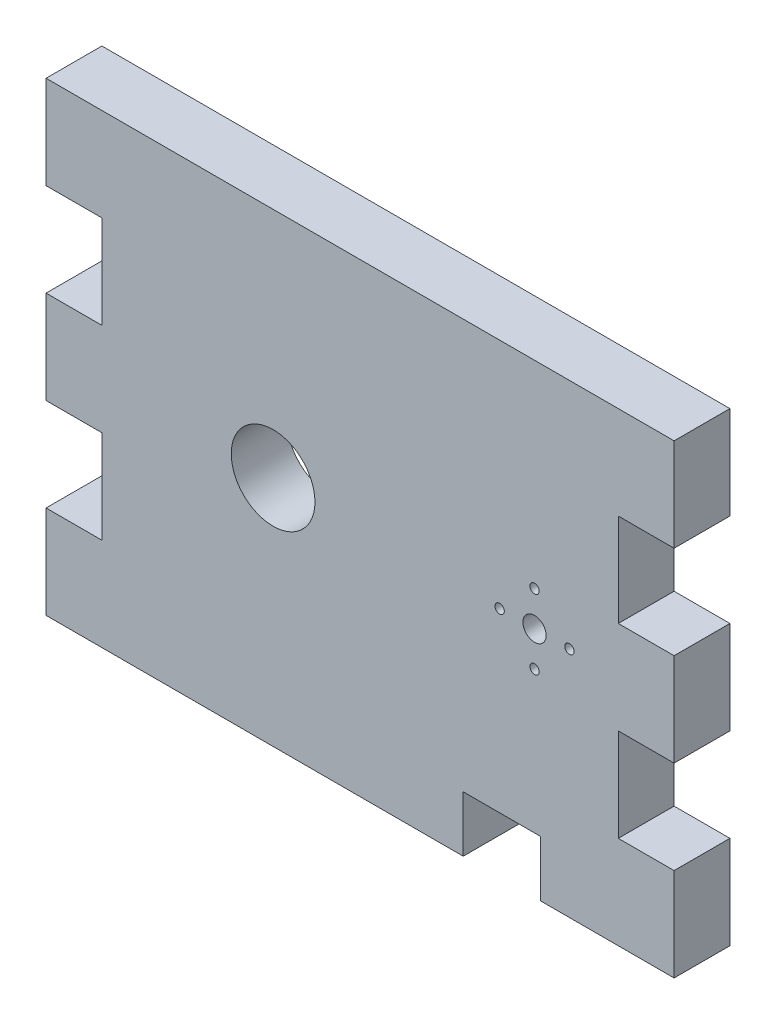
SolidWorks part; units mm, degrees
ref_plane "Front Plane" through (0, 0, 0) normal (0, 0, 1) x (1, 0, 0)
ref_plane "Top Plane" through (0, 0, 0) normal (0, 1, 0) x (1, 0, 0)
ref_plane "Right Plane" through (0, 0, 0) normal (1, 0, 0) x (0, 0, -1)
sketch "Sketch1" plane through (0, 0, 0) normal (0, 0, 1) x (1, 0, 0)
  line L1 (0, 0) -> (171.45, 0)
  line L2 (0, 0) -> (0, 127)
  line L3 (0, 127) -> (171.45, 127)
  line L4 (171.45, 0) -> (171.45, 127)
  dimension "D1" = 127
  dimension "D2" = 171.45
extrude "Boss-Extrude1" add sketch "Sketch1" along normal blind 15.24
sketch "Sketch5" plane through (0, 0, 15.24) normal (0, 0, 1) x (1, 0, 0)
  line L0 (0, 127) -> (0, 0) construction
  line L1 (0, 101.6) -> (15.24, 101.6)
  line L2 (0, 101.6) -> (0, 76.2)
  line L3 (0, 76.2) -> (15.24, 76.2)
  line L4 (15.24, 101.6) -> (15.24, 76.2)
  line L5 (171.45, 0) -> (171.45, 127) construction
  line L6 (0, 50.8) -> (15.24, 50.8)
  line L7 (0, 50.8) -> (0, 25.4)
  line L8 (0, 25.4) -> (15.24, 25.4)
  line L9 (15.24, 50.8) -> (15.24, 25.4)
  line L10 (171.45, 101.6) -> (156.21, 101.6)
  line L11 (171.45, 101.6) -> (171.45, 76.2)
  line L12 (171.45, 76.2) -> (156.21, 76.2)
  line L13 (156.21, 101.6) -> (156.21, 76.2)
  line L14 (15.24, 101.6) -> (15.24, 127) construction
  line L15 (171.45, 50.8) -> (156.21, 50.8)
  line L16 (171.45, 50.8) -> (171.45, 25.4)
  line L17 (171.45, 25.4) -> (156.21, 25.4)
  line L18 (156.21, 50.8) -> (156.21, 25.4)
  line L19 (171.45, 127) -> (0, 127) construction
  line L20 (15.24, 76.2) -> (15.24, 50.8) construction
  line L21 (15.24, 25.4) -> (15.24, 0) construction
  line L22 (0, 0) -> (171.45, 0) construction
  line L23 (156.21, 101.6) -> (156.21, 127) construction
  line L24 (156.21, 76.2) -> (156.21, 50.8) construction
  line L25 (156.21, 25.4) -> (156.21, 0) construction
  dimension "D1" = 15.24
  dimension "D2" = 15.24
sketch "Sketch6" plane through (0, 0, 15.24) normal (0, 0, 1) x (1, 0, 0)
extrude "Cut-Extrude1" cut sketch "Sketch5" against normal blind 15.24
sketch "Sketch7" plane through (0, 0, 15.24) normal (0, 0, 1) x (1, 0, 0)
  line L0 (0, 0) -> (171.45, 0) construction
  line L1 (113.8767, 0) -> (135.0433, 0)
  line L2 (113.8767, 0) -> (113.8767, 15.24)
  line L3 (113.8767, 15.24) -> (135.0433, 15.24)
  line L4 (135.0433, 0) -> (135.0433, 15.24)
  line L5 (113.8767, 15.24) -> (0, 15.24) construction
  line L6 (0, 25.4) -> (0, 0) construction
  line L8 (171.45, 0) -> (171.45, 25.4) construction
  point P6 (135.0433, 7.62)
  dimension "D3" = 15.24
  dimension "D1" = 21.1667
  dimension "D2" = 36.4067
sketch "Sketch11" plane through (0, 0, 15.24) normal (0, 0, 1) x (1, 0, 0)
  line L0 (171.45, 127) -> (0, 127) construction
  line L1 (0, 76.2) -> (0, 50.8) construction
  circle A0 centre (61.976, 63.5) radius 11.43
  point P4 (0, 63.5)
  dimension "D1" = 22.86
  dimension "D2" = 63.5
  dimension "D3" = 61.976
extrude "Cut-Extrude3" cut sketch "Sketch11" against normal blind 15.24
sketch "Sketch12" plane through (0, 0, 15.24) normal (0, 0, 1) x (1, 0, 0)
  line L0 (171.45, 127) -> (0, 127) construction
  line L2 (0, 127) -> (0, 101.6) construction
  circle A0 centre (133.35, 63.5) radius 3.175
  circle A1 centre (133.35, 73.025) radius 1.27
  circle A2 centre (142.875, 63.5) radius 1.27
  circle A3 centre (133.35, 53.975) radius 1.27
  circle A4 centre (123.825, 63.5) radius 1.27
  circle A5 centre (133.35, 63.5) radius 9.525 construction
  dimension "D1" = 2.54
  dimension "D2" = 6.35
  dimension "D3" = 2.54
  dimension "D4" = 2.54
  dimension "D5" = 2.54
  dimension "D8" = 19.05
  dimension "D6" = 63.5
  dimension "D7" = 133.35
extrude "Cut-Extrude4" cut sketch "Sketch12" against normal blind 15.24
extrude "Cut-Extrude5" cut sketch "Sketch7" against normal blind 15.24
equation "\"MDF\"= .6"
equation "\"Foamcore\"= .1"
equation "\"GMaterial\"= \"MDF\""
equation "\"D1@Boss-Extrude1\"=\"GMaterial\""
equation "\"D2@Sketch7\"=\"GMaterial\" + 2.5/3"
equation "\"D1@Cut-Extrude1\"=\"GMaterial\""
equation "\"D1@Cut-Extrude3\"=\"GMaterial\""
equation "\"D1@Cut-Extrude4\"=\"GMaterial\""
equation "\"D1@Cut-Extrude5\"=\"GMaterial\""
equation "\"D1@Sketch5\"=\"GMaterial\""
equation "\"D2@Sketch5\"=\"GMaterial\""
equation "\"D3@Sketch7\"=\"GMaterial\""
